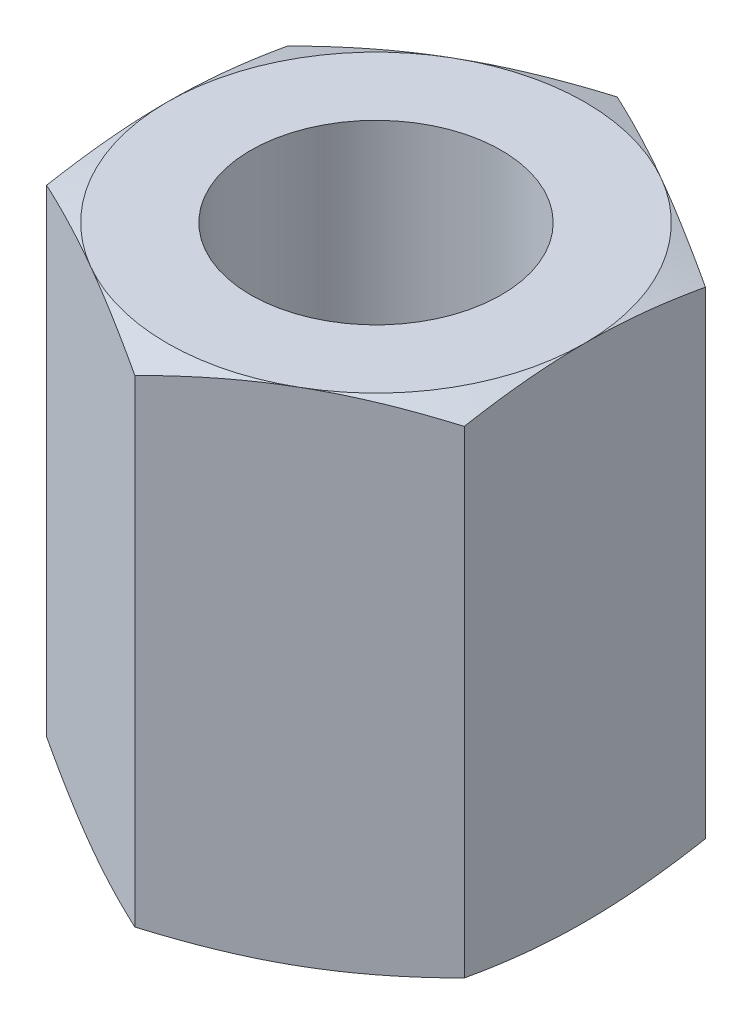
SolidWorks part; units mm, degrees
ref_plane "Front Plane" through (0, 0, 0) normal (0, 0, 1) x (1, 0, 0)
ref_plane "Top Plane" through (0, 0, 0) normal (0, 1, 0) x (1, 0, 0)
ref_plane "Right Plane" through (0, 0, 0) normal (1, 0, 0) x (0, 0, -1)
sketch "Sketch1" plane through (0, 0, 0) normal (0, 1, 0) x (1, 0, 0)
  line L1 (0, 2.8868) -> (-2.5, 1.4434)
  line L2 (-2.5, 1.4434) -> (-2.5, -1.4434)
  line L3 (-2.5, -1.4434) -> (0, -2.8868)
  line L4 (0, -2.8868) -> (2.5, -1.4434)
  line L5 (2.5, -1.4434) -> (2.5, 1.4434)
  line L6 (2.5, 1.4434) -> (0, 2.8868)
  circle A0 centre (0, 0) radius 2.5 construction
  circle A1 centre (0, 0) radius 1.5
  point P1 (2.5, 0)
  dimension "D2" = 3
  dimension "D1" = 5
extrude "Boss-Extrude1" add sketch "Sketch1" along normal blind 6
sketch "Sketch3" plane through (0, 6, 0) normal (0, 1, 0) x (1, 0, 0)
  circle A0 centre (0, 0) radius 2.5
ref_plane "Plane1" through (0, 0, 0) normal (-1, 0, 0) x (0, 0, 1)
sketch "Sketch6" plane through (0, 0, 0) normal (-1, 0, 0) x (0, 0, 1)
  line L0 (2.5, 6) -> (2.8868, 6)
  line L1 (1.4434, 6) -> (2.8868, 6) construction
  line L2 (2.5, 6) -> (-2.5, 6) construction
  line L3 (2.8868, 6) -> (2.8868, 5.8592)
  line L4 (2.8868, 6) -> (2.8868, 0) construction
  line L5 (2.8868, 5.8592) -> (2.5, 6)
  line L6 (0, 6) -> (0, 43.573) construction
  dimension "D1" = 20
  dimension "D2" = 0.3868
revolve "Cut-Revolve1" cut sketch "Sketch6" angle 360 about L6
ref_plane "Plane2" through (0, 3, 0) normal (0, 1, 0) x (1, 0, 0)
mirror "Mirror1" about plane through (0, 3, 0) normal (0, 1, 0) of "Cut-Revolve1"
